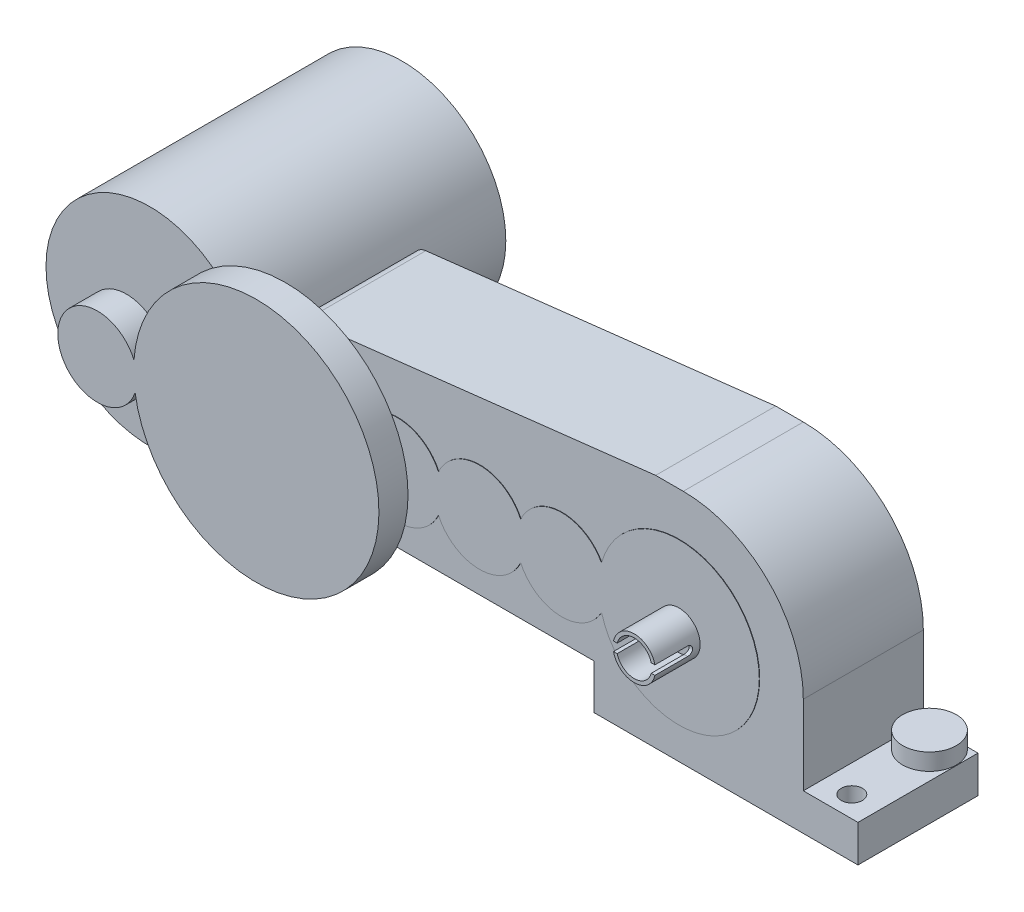
SolidWorks part; units mm, degrees
ref_plane "Front Plane" through (0, 0, 0) normal (0, 0, 1) x (1, 0, 0)
ref_plane "Top Plane" through (0, 0, 0) normal (0, 1, 0) x (1, 0, 0)
ref_plane "Right Plane" through (0, 0, 0) normal (1, 0, 0) x (0, 0, -1)
sketch "Sketch1" plane through (0, 0, 0) normal (0, 0, 1) x (1, 0, 0)
  line L0 (-2.4777, 0.4566) -> (-17.2605, 0.4566) construction
  line L1 (-17.2605, 0.4566) -> (-28.056, 6.8519) construction
  line L2 (-2.4777, 0.4566) -> (-2.4777, -10.951) construction
  line L4 (33.3871, 0.4566) -> (12.3051, 0.4566) construction
  line L5 (-2.4777, 0.4566) -> (12.3051, 0.4566) construction
  line L6 (-2.4777, 0.4566) -> (-15.0253, 0.4566) construction
  line L7 (-15.0253, 0.4566) -> (-31.5575, 0.4566) construction
  arc A0 (19.459, 4.3148) -> (4.9137, 3.8376) centre (12.3051, 0.4566) ccw
  arc A1 (4.9137, 3.8376) -> (-9.8691, 3.8376) centre (-2.4777, 0.4566) ccw
  arc A2 (19.459, -3.4017) -> (19.459, 4.3148) centre (33.3871, 0.4566) ccw
  arc A3 (4.9137, -2.9245) -> (19.459, -3.4017) centre (12.3051, 0.4566) ccw
  arc A4 (-9.8691, -2.9245) -> (4.9137, -2.9245) centre (-2.4777, 0.4566) ccw
  arc A5 (-25.3015, 1.6425) -> (-9.8691, -2.9245) centre (-17.2605, 0.4566) ccw
  arc A6 (-9.8691, 3.8376) -> (-22.1638, 6.939) centre (-17.2605, 0.4566) ccw
  arc A7 (19.459, -3.4017) -> (19.459, 4.3148) centre (33.3871, 0.4566) ccw construction
  arc A8 (-22.1638, 6.939) -> (-25.3015, 1.6425) centre (-28.056, 6.8519) ccw
  dimension "D2" = 16.256
  dimension "D4" = 90
  dimension "D5" = 28.9052
  dimension "D7" = 14.7828
  dimension "D8" = 14.7828
  dimension "D9" = 11.7856
  dimension "D3" = 16.256
  dimension "D6" = 149.357
  dimension "D10" = 12.5476
  dimension "D13" = 12.5476
  dimension "D14" = 21.082
extrude "Extrude1" add sketch "Sketch1" along normal mid plane 21.7424
sketch "Sketch3" plane through (0, 0, 0) normal (0, 0, 1) x (1, 0, 0)
  circle A0 centre (33.3871, 0.4566) radius 3.81
  circle A1 centre (33.3871, 0.4566) radius 3.1707
  dimension "D1" = 7.62
extrude "Extrude2" add sketch "Sketch3" along normal mid plane 37.846
sketch "Sketch4" plane through (0, 0, 0) normal (0, 0, 1) x (1, 0, 0)
  line L0 (-33.8117, 15.4645) -> (29.1227, 22.7393)
  line L1 (-45.3134, -19.7615) -> (-27.4794, -19.7615)
  line L2 (-36.06, -13.1207) -> (-36.06, 12.9413)
  line L3 (29.1227, 22.7393) -> (34.0855, 22.7393)
  line L4 (55.6755, -13.1207) -> (55.6755, 1.1493)
  line L5 (65.5063, -19.7615) -> (65.5063, -13.1207)
  line L6 (65.5063, -13.1207) -> (55.6755, -13.1207)
  line L7 (-45.3134, -19.7615) -> (-45.3134, -13.1207)
  line L8 (-36.06, -13.1207) -> (-45.3134, -13.1207)
  line L9 (-27.4794, -11.7143) -> (18.0583, -11.7143)
  line L10 (18.0583, -11.7143) -> (18.0583, -19.7615)
  line L11 (-27.4794, -11.7143) -> (-27.4794, -19.7615)
  line L12 (18.0583, -19.7615) -> (65.5063, -19.7615)
  circle A0 centre (33.3871, 0.4566) radius 22.0726 construction
  arc A1 (-36.06, 12.9413) -> (-33.8117, 15.4645) centre (-33.52, 12.9413) cw
  arc A2 (34.0855, 22.7393) -> (55.6755, 1.1493) centre (34.0855, 1.1493) cw
  dimension "D3" = 6.6408
  dimension "D4" = 21.59
  dimension "D2" = 2.54
  dimension "D1" = 19.7615
  dimension "D5" = 42.5008
  dimension "D6" = 91.7356
extrude "Extrude3" add sketch "Sketch4" along normal mid plane 21.59 separate body
sketch "Sketch6" plane through (0, 0, 0) normal (0, 1, 0) x (1, 0, 0)
  line L0 (-40.6867, 10.795) -> (-40.6867, -25.6603) construction
  line L1 (-36.06, 10.795) -> (-45.3134, 10.795) construction
  line L2 (-29.4475, 6.985) -> (79.3394, 6.985) construction
  line L3 (60.5909, 10.795) -> (60.5909, -18.8958) construction
  line L4 (65.5063, 10.795) -> (55.6755, 10.795) construction
  line L5 (-45.3134, 0) -> (81.1858, 0) construction
  line L6 (-45.3134, -10.795) -> (-45.3134, 10.795) construction
  circle A0 centre (-40.6867, 6.985) radius 1.905
  circle A1 centre (60.5909, 6.985) radius 1.905
  circle A2 centre (60.5909, -6.985) radius 1.905
  circle A3 centre (-40.6867, -6.985) radius 1.905
  dimension "D2" = 3.81
  dimension "D1" = 3.81
extrude "Extrude4" cut sketch "Sketch6" against normal blind 21.59
sketch "Sketch7" plane through (0, 0, 0) normal (0, 0, 1) x (1, 0, 0)
  circle A0 centre (-28.056, 6.8519) radius 1.27
  dimension "D1" = 2.54
extrude "Extrude5" add sketch "Sketch7" along normal blind 18.669
sketch "Sketch8" plane through (0, 0, 0) normal (1, 0, 0) x (0, 0, -1)
  line L0 (-18.923, 0.4566) -> (-7.5479, 0.4566) construction
  line L1 (-18.923, 4.2666) -> (-18.923, -3.3534) construction
  line L2 (-13.0321, 1.275) -> (-21.0971, 1.275)
  line L3 (-21.0971, 1.275) -> (-21.0971, -0.3619)
  line L4 (-13.0321, -0.3619) -> (-21.0971, -0.3619)
  line L5 (0, 14.6282) -> (0, -4.8149) construction
  line L6 (13.0321, -0.3619) -> (21.0971, -0.3619)
  line L7 (21.0971, 1.275) -> (21.0971, -0.3619)
  line L8 (13.0321, 1.275) -> (21.0971, 1.275)
  arc A0 (-13.0321, -0.3619) -> (-13.0321, 1.275) centre (-13.0321, 0.4566) ccw
  arc A1 (13.0321, -0.3619) -> (13.0321, 1.275) centre (13.0321, 0.4566) cw
  point P10 (-21.0971, 0.4566)
  point P18 (21.0971, 0.4566)
extrude "Extrude6" cut sketch "Sketch8" against normal blind 10 from offset 38.1
sketch "Sketch9" plane through (0, 0, 18.669) normal (0, 0, 1) x (1, 0, 0)
  circle A0 centre (-28.056, 6.8519) radius 15.5829
  dimension "D1" = 31.1658
extrude "Extrude7" add sketch "Sketch9" along normal blind 1.5494
sketch "Sketch10" plane through (0, 0, 20.2184) normal (0, 0, 1) x (1, 0, 0)
  line L0 (-28.056, 6.8519) -> (-56.6324, 5.6816) construction
  line L1 (-28.056, 6.8519) -> (-28.056, 9.5882) construction
  arc A0 (-49.8566, 3.4795) -> (-50.0593, 8.4304) centre (-28.056, 6.8519) ccw
  arc A1 (-50.0593, 8.4304) -> (-49.8566, 3.4795) centre (-56.6324, 5.6816) ccw
  circle A2 centre (-56.6324, 5.6816) radius 18.669 construction
  dimension "D1" = 44.1198
  dimension "D3" = 14.2494
  dimension "D4" = 37.338
  dimension "D2" = 28.6004
  dimension "D5" = 92.345
extrude "Extrude8" add sketch "Sketch10" along normal blind 5.2324
sketch "Sketch11" plane through (0, 0, 20.2184) normal (0, 0, -1) x (-1, 0, 0)
  circle A0 centre (56.6324, 5.6816) radius 18.669
  dimension "D1" = 37.338
extrude "Extrude9" add sketch "Sketch11" along normal blind 45.3644 from offset 4.191 separate body
sketch "Sketch12" [suppressed] plane through (0, 0, 18.669) normal (0, 0, -1) x (-1, 0, 0)
  circle A0 centre (28.056, 6.8519) radius 26.3779
  dimension "D1" = 52.7558
sketch "Sketch14" plane through (0, -13.1207, 0) normal (0, 1, 0) x (1, 0, 0)
  circle A0 centre (60.5909, 6.985) radius 4.826
  circle A1 centre (-41.1748, 6.985) radius 4.826
  dimension "D1" = 9.652
  dimension "D2" = 9.652
extrude "Extrude10" add sketch "Sketch14" along normal blind 3.0226 separate body
